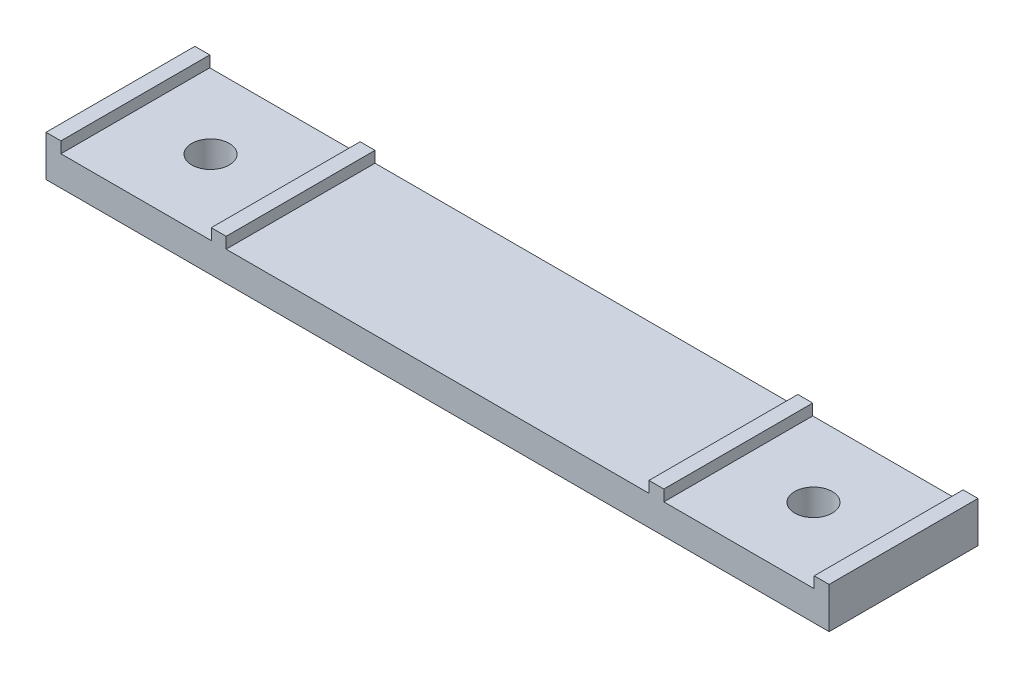
SolidWorks part; units mm, degrees
ref_plane "Front Plane" through (0, 0, 0) normal (0, 0, 1) x (1, 0, 0)
ref_plane "Top Plane" through (0, 0, 0) normal (0, 1, 0) x (1, 0, 0)
ref_plane "Right Plane" through (0, 0, 0) normal (1, 0, 0) x (0, 0, -1)
sketch "Sketch2" plane through (0, 0, 0) normal (0, 0, 1) x (1, 0, 0)
  line L0 (0, 0) -> (0, 29.464) construction
  line L1 (0, 29.464) -> (-45.6777, 29.464) construction
  line L2 (66.802, 0) -> (-66.802, 0)
  line L3 (-66.802, 0) -> (-66.802, 6.985)
  line L4 (-66.802, 6.985) -> (-64.262, 6.985)
  line L5 (-64.262, 6.985) -> (-64.262, 5.08)
  line L6 (-64.262, 5.08) -> (-38.608, 5.08)
  line L7 (-38.608, 5.08) -> (-38.608, 6.985)
  line L8 (-38.608, 6.985) -> (-36.068, 6.985)
  line L9 (-36.068, 6.985) -> (-36.068, 5.08)
  line L10 (-36.068, 5.08) -> (36.068, 5.08)
  line L11 (36.068, 6.985) -> (36.068, 5.08)
  line L12 (38.608, 6.985) -> (36.068, 6.985)
  line L13 (38.608, 5.08) -> (38.608, 6.985)
  line L14 (64.262, 5.08) -> (38.608, 5.08)
  line L15 (64.262, 6.985) -> (64.262, 5.08)
  line L16 (66.802, 6.985) -> (64.262, 6.985)
  line L17 (66.802, 0) -> (66.802, 6.985)
  point P13 (-51.435, 5.08)
  point P14 (-48.2721, 7.5978)
  point P15 (-55.4178, 6.985)
  point P17 (0, 5.08)
  point P24 (51.435, 5.08)
  dimension "D1" = 5.08
  dimension "D2" = 51.435
  dimension "D3" = 2.54
  dimension "D4" = 1.905
  dimension "D5" = 25.654
extrude "Boss-Extrude1" add sketch "Sketch2" along normal blind 25.4
sketch "Sketch3" plane through (0, 5.08, 0) normal (0, 1, 0) x (1, 0, 0)
  line L0 (-64.262, -25.4) -> (-64.262, 0) construction
  line L1 (-38.608, -25.4) -> (-64.262, -25.4) construction
  line L2 (64.262, -25.4) -> (38.608, -25.4) construction
  circle A0 centre (-51.435, -12.7) radius 3.2004
  circle A1 centre (51.435, -12.7) radius 3.2004
  point P4 (-64.262, -12.7)
  point P5 (-51.435, -25.4)
  point P8 (51.435, -25.4)
  point P11 (51.435, -6.6474)
  point P14 (0, 0)
  dimension "D1" = 6.4008
extrude "Cut-Extrude1" cut sketch "Sketch3" against normal blind 25.4
